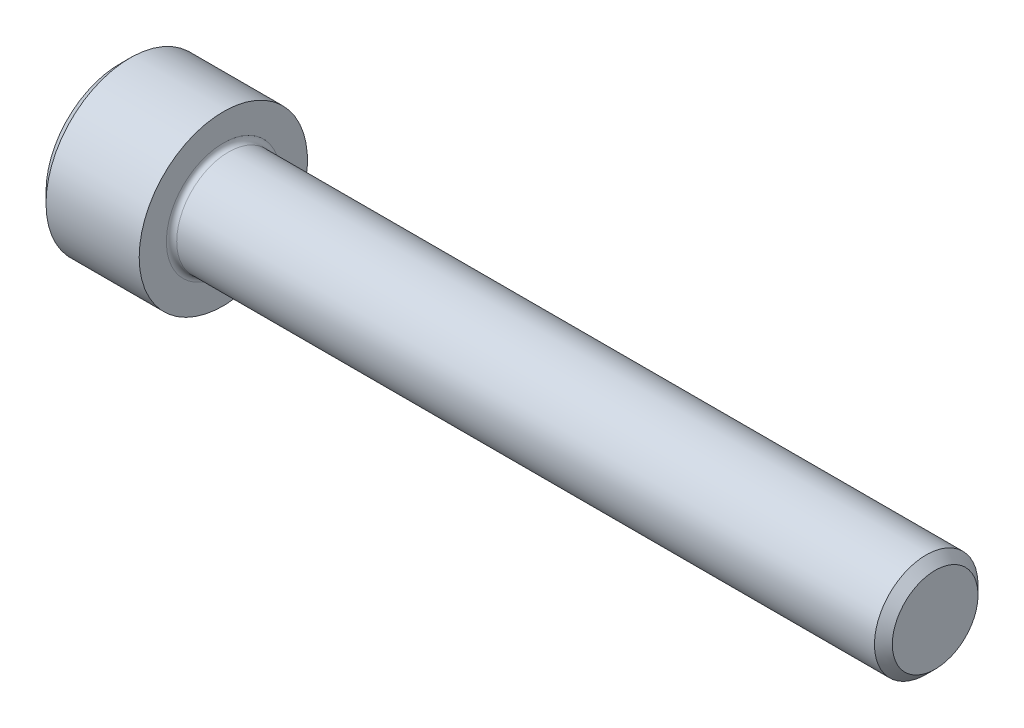
SolidWorks part; units mm, degrees
ref_plane "Plane1" through (0, 0, 0) normal (0, 0, 1) x (1, 0, 0)
ref_plane "Plane2" through (0, 0, 0) normal (0, 1, 0) x (1, 0, 0)
ref_plane "Plane3" through (0, 0, 0) normal (1, 0, 0) x (0, 0, -1)
sketch "BodySke" plane through (0, 0, 0) normal (0, 0, 1) x (1, 0, 0)
  line L0 (0, 0) -> (0, 5.7)
  line L1 (0.8, 6.5) -> (8, 6.5)
  line L2 (8, 6.5) -> (8, 4)
  line L3 (8, 4) -> (62.3095, 4)
  line L4 (63, 3.3095) -> (63, 0)
  line L5 (63, 0) -> (0, 0)
  line L6 (-31.75, 0) -> (127, 0) construction
  line L7 (0, 5.7) -> (0.8, 6.5)
  line L8 (63, 3.3095) -> (62.3095, 4)
  line L9 (0, -5.7) -> (0.8, -6.5) construction
  line L10 (63, -3.3095) -> (62.3095, -4) construction
  line L11 (9.25, 9.525) -> (9.25, 3.175) construction
  line L12 (35, 9.525) -> (35, 3.175) construction
  line L13 (13, 9.525) -> (13, 3.175) construction
  dimension "Diameter" = 8
  dimension "Head_ht" = 8
  dimension "Length" = 55
  dimension "Body_ch_ang" = 45
  dimension "Head_dia" = 13
  dimension "Head_ch_ang" = 45
  dimension "Minor_dia" = 6.619
  dimension "Advance" = 1.25
  dimension "Thread_nom" = 28
  dimension "Thread_length" = 50
  dimension "Head_ch_ht" = 0.8
revolve "Base-Revolve" add sketch "BodySke"
cosmetic thread "ThreadCosmetic"
fillet "Fillet1" radius 0.4 1 edges at (8, 0, 4)
sketch "Sketch2" plane through (0, 0, 0) normal (0, 0, 1) x (1, 0, 0)
  line L0 (0, 3.0475) -> (4, 3.0475)
  line L1 (4, 3.0475) -> (5.7595, 0)
  line L2 (-31.75, 0) -> (127, 0) construction
  line L3 (5.7595, 0) -> (0, 0)
  line L4 (0, 0) -> (0, 3.0475)
  line L5 (0, 5.7) -> (0, -5.7) construction
  line L6 (0, 0) -> (47.625, 0) construction
  line L7 (8, -6.5) -> (8, 6.5) construction
  dimension "D1" = 3.0475
  dimension "D2" = 60
  dimension "Wall_thickness" = 4
revolve "Hex-PreBroach" cut sketch "Sketch2" angle 360 about L6
sketch "Sketch3" plane through (0, 0, 0) normal (-1, 0, 0) x (0, 0.5, 0.866)
  line L0 (1.7595, 3.0475) -> (-1.7595, 3.0475)
  line L1 (-1.7595, 3.0475) -> (-3.5189, 0)
  line L2 (1.7595, 3.0475) -> (3.5189, 0)
  line L3 (1.7595, -3.0475) -> (3.5189, 0)
  line L4 (1.7595, -3.0475) -> (-1.7595, -3.0475)
  line L5 (-1.7595, -3.0475) -> (-3.5189, 0)
  dimension "D1" = 3.0475
  dimension "D2" = 3.0475
  dimension "Hex_size" = 6.095
extrude "Hex" cut sketch "Sketch3" against normal blind 4
sketch "Sketch4" plane through (0, 0, 0) normal (-1, 0, 0) x (0, 0, 1)
  line L0 (0, 0) -> (3.7846, 0)
  line L1 (0, 0) -> (6.1484, 3.5498) construction
  line L2 (0, 0) -> (1.8923, 3.2776)
  line L3 (3.1235, 0.8061) -> (3.6229, 1.0945)
  line L4 (2.2599, 2.3019) -> (2.7593, 2.5903)
  arc A0 (3.1235, 0.8061) -> (2.2599, 2.3019) centre (0, 0) ccw
  arc A1 (3.7846, 0) -> (3.6229, 1.0945) centre (0, 0) ccw
  arc A2 (1.8923, 3.2776) -> (2.7593, 2.5903) centre (0, 0) cw
  dimension "D1" = 30
  dimension "Spline_n_dim" = 6.4516
  dimension "Spline_m_dim" = 7.5692
  dimension "D2" = 60
  dimension "D3" = 0.8636
  dimension "Spline_p_dim" = 1.7272
extrude "Spline" [suppressed] cut sketch "Sketch4" against normal blind 4
pattern_circular "CirPattern1" [suppressed] count 6 every 60
sketch "Sketch5" plane through (0, 0, 0) normal (0, 0, 1) x (1, 0, 0)
  line L0 (-31.75, 0) -> (127, 0) construction
  line L2 (0, 5.7) -> (0, -5.7) construction
  circle A0 centre (2.7, 0) radius 0.675
  dimension "Drilled_hole_dia" = 1.35
  dimension "Drilled_hole_loc" = 2.7
extrude "Hole" [suppressed] cut sketch "Sketch5" against normal through all and the other way through all
pattern_circular "Drilled-4" [suppressed] count 2 every 60
pattern_circular "Drilled-6" [suppressed] count 3 every 60
sketch "ThdSchSke" plane through (0, 0, 0) normal (0, 0, 1) x (1, 0, 0)
  line L0 (35, -3.3095) -> (34.5165, -4)
  line L1 (35, -3.3095) -> (35.4835, -4)
  line L2 (35.4835, -4) -> (35.4835, -5)
  line L3 (-3.175, 0) -> (5.1513, 0) construction
  line L5 (35.4835, -5) -> (34.5165, -5)
  line L6 (34.5165, -5) -> (34.5165, -4)
  line L7 (0, 5.7) -> (0, -5.7) construction
  dimension "Thread_minor" = 6.619
  dimension "Diameter" = 8
  dimension "Start" = 35
  dimension "SideAngle" = 55
  dimension "VeeAngle" = 70
  dimension "Overcut" = 10
revolve "ThreadSchematic" [suppressed] cut sketch "ThdSchSke" angle 360 about L3
pattern_linear "ThdSchPat" [suppressed]
equation "\"D2@Sketch3\" = \"Hex_size@Sketch3\" / 2"
equation "\"D1@Sketch3\" = \"Hex_size@Sketch3\" / 2"
equation "\"D1@Sketch2\" = \"Hex_size@Sketch3\" / 2"
equation "\"D3@Sketch4\" = \"Spline_p_dim@Sketch4\" / 2"
equation "\"Thread_minor@ThreadCosmetic\"  =  \"Minor_dia@BodySke\""
equation "\"D2@CirPattern1\" = 360 / \"Num_teeth@CirPattern1\""
equation "\"Wall_thickness@Sketch2\" = \"Head_ht@BodySke\" - \"Key_eng@Hex\""
equation "\"Thread_length@ThreadCosmetic\" = ((sgn( (\"Length@BodySke\" - \"Advance@BodySke\" ) - \"Thread_nom@BodySke\" )-1)*( (\"Length@BodySke\" - \"Advance@BodySke\" ) - \"Thread_nom@BodySke\" ))/-2+ \"Thread_nom@BodySke\""
equation "\"Thread_minor@ThdSchSke\" = \"Minor_dia@BodySke\""
equation "\"Diameter@ThdSchSke\" = \"Diameter@BodySke\""
equation "\"Overcut@ThdSchSke\" = \"Diameter@BodySke\" * 1.25"
equation "\"Start@ThdSchSke\" = \"Head_ht@BodySke\" + \"Length@BodySke\" - \"Thread_length@ThreadCosmetic\"  '---Non-countersunk---"
equation "\"Num_threads@ThdSchPat\" = int( \"Thread_length@ThreadCosmetic\" / \"Advance@BodySke\" + 0.999 )  + 1"
equation "\"Advance@ThdSchPat\" = \"Thread_length@ThreadCosmetic\" /  (\"Num_threads@ThdSchPat\" - 1) 'relax it"
equation "\"Num_threads@ThdSchPat\" = \"Num_threads@ThdSchPat\" - sgn( \"Num_threads@ThdSchPat\" - 1) '---chamfered tips only---"
